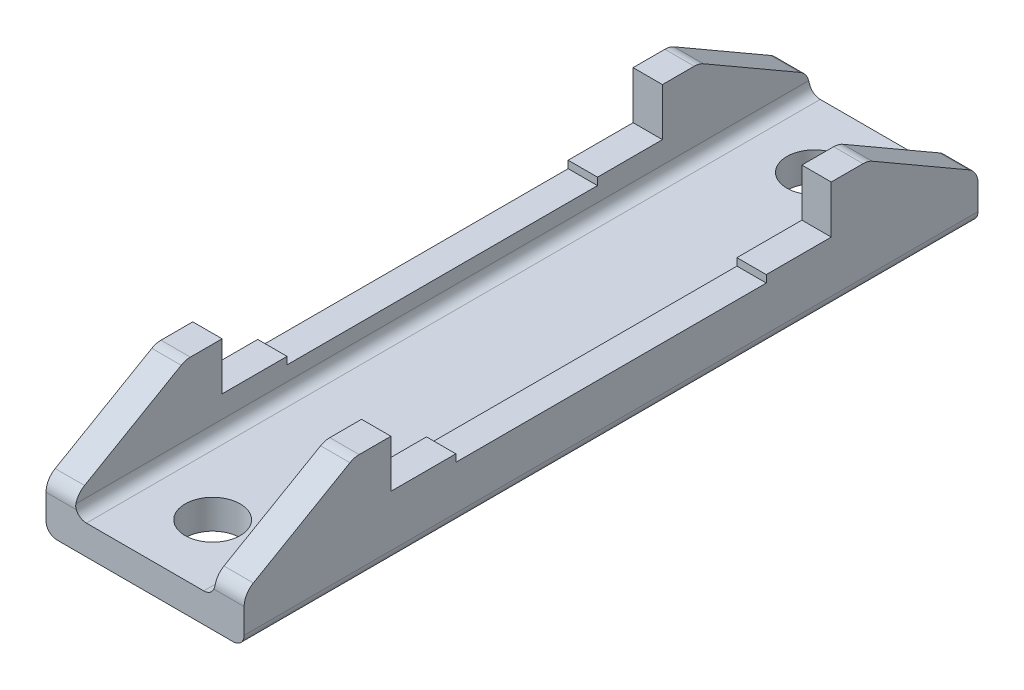
SolidWorks part; units mm, degrees
material "1.0044 (S275JR)"
ref_plane "Płaszczyzna przednia" through (0, 0, 0) normal (0, 0, 1) x (1, 0, 0)
ref_plane "Płaszczyzna górna" through (0, 0, 0) normal (0, 1, 0) x (1, 0, 0)
ref_plane "Płaszczyzna prawa" through (0, 0, 0) normal (1, 0, 0) x (0, 0, -1)
sketch "Szkic1" plane through (0, 0, 0) normal (1, 0, 0) x (0, 0, -1)
  line L0 (0, 0) -> (-8.6603, 0)
  line L1 (-11.1603, -0.6699) -> (-37.5, -15.8771)
  line L2 (-40, -20.2073) -> (-40, -30)
  line L3 (60, 38.3157) -> (60, -85.3118) construction
  line L4 (17.7, -15) -> (102.3, -15)
  line L5 (-40, -30) -> (160, -30)
  line L6 (120, -13) -> (120, 0)
  line L7 (102.3, -13) -> (120, -13)
  line L8 (102.3, -15) -> (102.3, -13)
  line L9 (160, -20.2073) -> (160, -30)
  line L10 (131.1603, -0.6699) -> (157.5, -15.8771)
  line L11 (17.7, -15) -> (17.7, -13)
  line L12 (17.7, -13) -> (0, -13)
  line L13 (0, -13) -> (0, 0)
  line L14 (120, 0) -> (128.6603, 0)
  arc A0 (128.6603, 0) -> (131.1603, -0.6699) centre (128.6603, -5) cw
  arc A1 (157.5, -15.8771) -> (160, -20.2073) centre (155, -20.2073) cw
  arc A6 (-37.5, -15.8771) -> (-40, -20.2073) centre (-35, -20.2073) ccw
  arc A7 (-8.6603, 0) -> (-11.1603, -0.6699) centre (-8.6603, -5) ccw
  point P6 (60, -15)
  point P7 (130, 0)
  point P23 (60, -30)
  point P38 (-10, 0)
  dimension "D2" = 60
  dimension "D3" = 2
  dimension "D5" = 5
  dimension "D4" = 30
  dimension "D6" = 10
  dimension "D7" = 120
  dimension "D12" = 40
  dimension "D13" = 17.7
  dimension "D16" = 13
extrude "Dodanie-wyciągnięcie1" add sketch "Szkic1" along normal blind 8
ref_plane "Płaszczyzna1" through (-19, 0, 0) normal (-1, 0, 0) x (0, 0, 1)
mirror "Lustro3" about plane through (-19, 0, 0) normal (-1, 0, 0) of bodies 101 102
sketch "Szkic2" plane through (0, 0, 0) normal (-1, 0, 0) x (0, 0, 1)
  line L0 (-160, -30) -> (-160, -20.2073) construction
  line L1 (40, -30) -> (-160, -30)
  line L2 (40, -30) -> (40, -22)
  line L3 (40, -22) -> (-160, -22)
  line L4 (-160, -30) -> (-160, -22)
  dimension "D1" = 8
extrude "Dodanie-wyciągnięcie2" add sketch "Szkic2" along normal up to next
fillet "Zaokrąglenie1" radius 3 2 edges at (8, -30, -60) (-46, -30, -60)
fillet "Zaokrąglenie2" radius 3 2 edges at (0, -22, -60) (-38, -22, -60)
sketch "Szkic3" plane through (0, -30, 0) normal (0, -1, 0) x (1, 0, 0)
  line L0 (5, -160) -> (-43, -160) construction
  line L1 (5, 40) -> (-43, 40) construction
  circle A0 centre (-18.5803, 22) radius 7.5
  circle A1 centre (-18.5803, -142) radius 7.5
  dimension "D1" = 15
  dimension "D2" = 15
  dimension "D3" = 18
  dimension "D4" = 18
extrude "Wytnij-wyciągnięcie1" cut sketch "Szkic3" against normal through all
